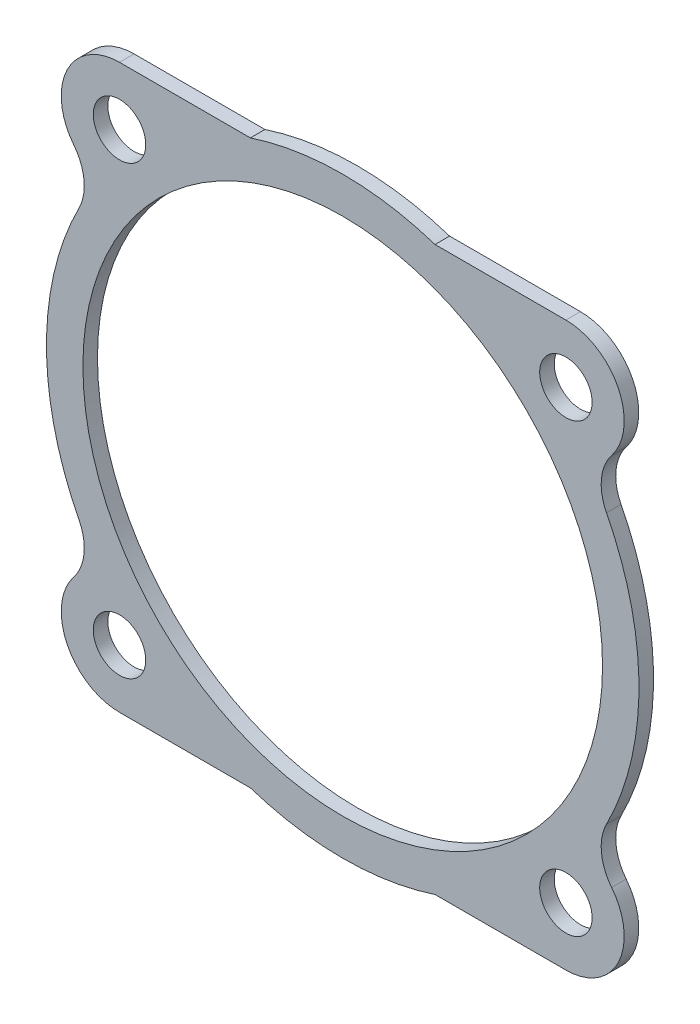
SolidWorks part; units mm, degrees
ref_plane "XZ (Face)" through (0, 0, 0) normal (0, 0, 1) x (1, 0, 0)
ref_plane "XY (Dessus)" through (0, 0, 0) normal (0, 1, 0) x (1, 0, 0)
ref_plane "YZ (Droite)" through (0, 0, 0) normal (1, 0, 0) x (0, 0, -1)
sketch "Esquisse1" plane through (0, 0, 0) normal (0, 0, 1) x (1, 0, 0)
  line L4 (-4.7527, 14.4905) -> (-11.4905, 14.4905)
  line L5 (-11.4905, -14.4905) -> (-4.7527, -14.4905)
  line L6 (4.7527, -14.4905) -> (11.4905, -14.4905)
  line L7 (11.4905, 14.4905) -> (4.7527, 14.4905)
  line L8 (-4.7527, 14.4905) -> (-11.4905, 14.4905)
  line L9 (-11.4905, -14.4905) -> (-4.7527, -14.4905)
  line L10 (4.7527, -14.4905) -> (11.4905, -14.4905)
  line L11 (11.4905, 14.4905) -> (4.7527, 14.4905)
  circle A1 centre (0, 0) radius 13.375 construction
  circle A2 centre (0, 0) radius 13.375
  arc A17 (4.7527, 14.4905) -> (0, 15.25) centre (0, 0) ccw
  arc A18 (0, 15.25) -> (-4.7527, 14.4905) centre (0, 0) ccw
  arc A19 (-11.4905, 14.4905) -> (-13.8437, 9.6298) centre (-11.4905, 11.4905) ccw
  arc A20 (-13.5787, 6.9412) -> (-13.8437, 9.6298) centre (-15.8047, 8.0792) ccw
  arc A21 (-13.5787, 6.9412) -> (-14.766, 3.8116) centre (0, 0) ccw
  arc A22 (-14.766, 3.8116) -> (-15.1104, 2.0591) centre (0, 0) ccw
  arc A23 (-15.1104, 2.0591) -> (-15.25, 0) centre (0, 0) ccw
  arc A24 (-15.25, 0) -> (-13.5787, -6.9412) centre (0, 0) ccw
  arc A25 (-13.8437, -9.6298) -> (-13.5787, -6.9412) centre (-15.8047, -8.0792) ccw
  arc A26 (-13.8437, -9.6298) -> (-11.4905, -14.4905) centre (-11.4905, -11.4905) ccw
  arc A27 (-4.7527, -14.4905) -> (4.7527, -14.4905) centre (0, 0) ccw
  arc A28 (11.4905, -14.4905) -> (13.8437, -9.6298) centre (11.4905, -11.4905) ccw
  arc A29 (13.5787, -6.9412) -> (13.8437, -9.6298) centre (15.8047, -8.0792) ccw
  arc A30 (13.5787, -6.9412) -> (13.5787, 6.9412) centre (0, 0) ccw
  arc A31 (13.8437, 9.6298) -> (13.5787, 6.9412) centre (15.8047, 8.0792) ccw
  arc A32 (13.8437, 9.6298) -> (11.4905, 14.4905) centre (11.4905, 11.4905) ccw
  arc A33 (4.7527, 14.4905) -> (0, 15.25) centre (0, 0) ccw
  arc A34 (0, 15.25) -> (-4.7527, 14.4905) centre (0, 0) ccw
  arc A35 (-11.4905, 14.4905) -> (-13.8437, 9.6298) centre (-11.4905, 11.4905) ccw
  arc A36 (-13.5787, 6.9412) -> (-13.8437, 9.6298) centre (-15.8047, 8.0792) ccw
  arc A37 (-13.5787, 6.9412) -> (-14.766, 3.8116) centre (0, 0) ccw
  arc A38 (-14.766, 3.8116) -> (-15.1104, 2.0591) centre (0, 0) ccw
  arc A39 (-15.1104, 2.0591) -> (-15.25, 0) centre (0, 0) ccw
  arc A40 (-15.25, 0) -> (-13.5787, -6.9412) centre (0, 0) ccw
  arc A41 (-13.8437, -9.6298) -> (-13.5787, -6.9412) centre (-15.8047, -8.0792) ccw
  arc A42 (-13.8437, -9.6298) -> (-11.4905, -14.4905) centre (-11.4905, -11.4905) ccw
  arc A43 (-4.7527, -14.4905) -> (4.7527, -14.4905) centre (0, 0) ccw
  arc A44 (11.4905, -14.4905) -> (13.8437, -9.6298) centre (11.4905, -11.4905) ccw
  arc A45 (13.5787, -6.9412) -> (13.8437, -9.6298) centre (15.8047, -8.0792) ccw
  arc A46 (13.5787, -6.9412) -> (13.5787, 6.9412) centre (0, 0) ccw
  arc A47 (13.8437, 9.6298) -> (13.5787, 6.9412) centre (15.8047, 8.0792) ccw
  arc A48 (13.8437, 9.6298) -> (11.4905, 14.4905) centre (11.4905, 11.4905) ccw
  circle A52 centre (-11.4905, -11.4905) radius 1.35
  circle A53 centre (-11.4905, -11.4905) radius 1.35
  circle A55 centre (-11.4905, 11.4905) radius 1.35
  circle A56 centre (-11.4905, 11.4905) radius 1.35
  circle A58 centre (11.4905, 11.4905) radius 1.35
  circle A59 centre (11.4905, 11.4905) radius 1.35
  circle A61 centre (11.4905, -11.4905) radius 1.35
  circle A62 centre (11.4905, -11.4905) radius 1.35
  dimension "D2" = 0.1
  dimension "D3" = 0.1
  dimension "D1" = 0
  dimension "D4" = 0.1
  dimension "D5" = 0.1
extrude "Base-Extrusion" add sketch "Esquisse1" along normal blind 0.75
